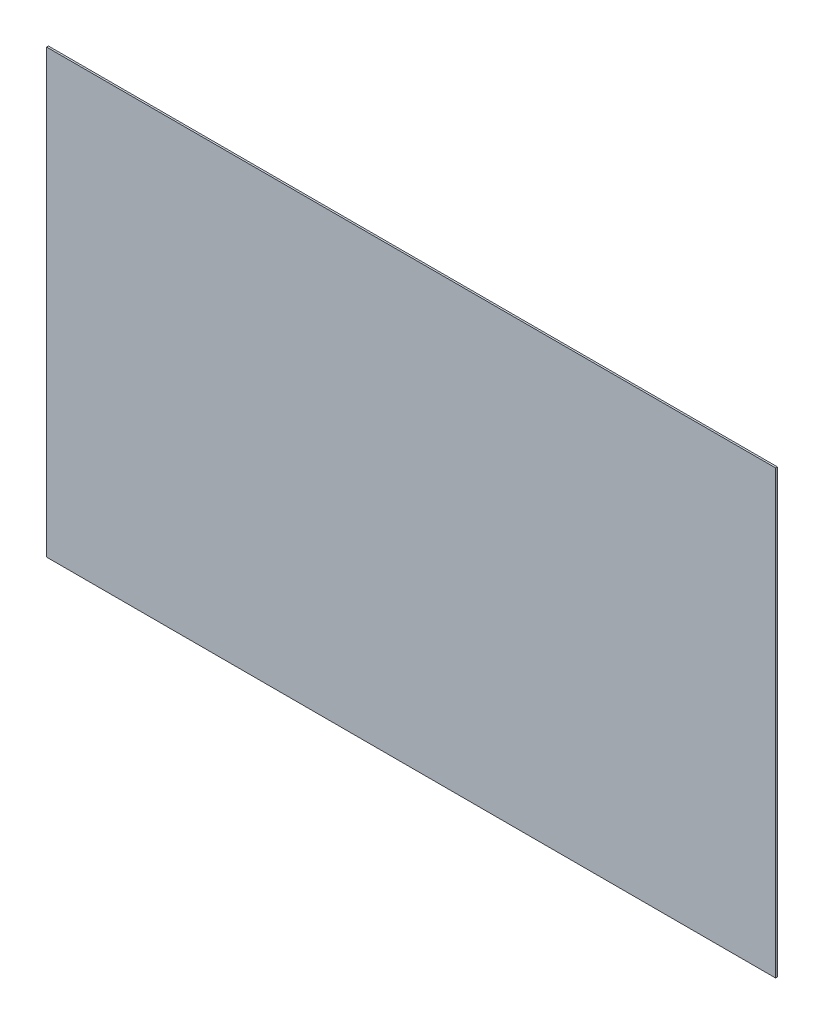
SolidWorks part; units mm, degrees
ref_plane "Front Plane" through (0, 0, 0) normal (0, 0, 1) x (1, 0, 0)
ref_plane "Top Plane" through (0, 0, 0) normal (0, 1, 0) x (1, 0, 0)
ref_plane "Right Plane" through (0, 0, 0) normal (1, 0, 0) x (0, 0, -1)
sketch "Sketch1" plane through (0, 0, 0) normal (0, 0, 1) x (1, 0, 0)
  line L1 (0, 0) -> (628.65, 0)
  line L2 (0, 0) -> (0, 381)
  line L3 (0, 381) -> (628.65, 381)
  line L4 (628.65, 0) -> (628.65, 381)
  dimension "D1" = 381
  dimension "D2" = 628.65
extrude "Boss-Extrude1" add sketch "Sketch1" along normal blind 1.5875
